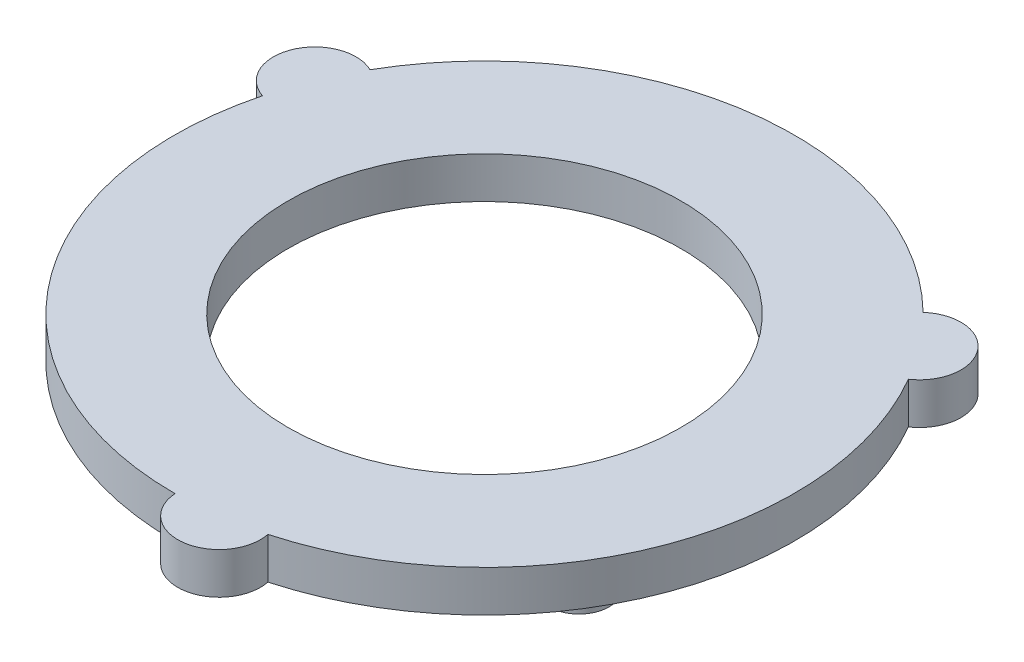
SolidWorks part; units mm, degrees
ref_plane "Спереди" through (0, 0, 0) normal (0, 0, 1) x (1, 0, 0)
ref_plane "Сверху" through (0, 0, 0) normal (0, 1, 0) x (1, 0, 0)
ref_plane "Справа" through (0, 0, 0) normal (1, 0, 0) x (0, 0, -1)
sketch "Sketch1" plane through (0, 0, 0) normal (0, 1, 0) x (1, 0, 0)
  circle A0 centre (0, 0) radius 19
  dimension "D1" = 38
extrude "Boss-Extrude1" add sketch "Sketch1" along normal blind 3.5
sketch "Sketch2" plane through (0, 0, 0) normal (0, 1, 0) x (1, 0, 0)
  circle A0 centre (0, 0) radius 30
  circle A1 centre (0, 0) radius 19
  circle A2 centre (0, 0) radius 25 construction
  circle A3 centre (0, 25) radius 2.8
  circle A4 centre (21.6506, -12.5) radius 2.8
  circle A5 centre (-21.6506, -12.5) radius 2.8
  point P16 (0, 0)
  dimension "D2" = 50
  dimension "D1" = 3
extrude "Boss-Extrude2" add sketch "Sketch2" along normal blind 4
sketch "Sketch3" plane through (0, 3.5, 0) normal (0, 1, 0) x (1, 0, 0)
  circle A0 centre (0, 0) radius 19
extrude "Cut-Extrude1" cut sketch "Sketch3" against normal blind 10
sketch "Sketch4" plane through (0, 0, 0) normal (0, -1, 0) x (1, 0, 0)
  circle A0 centre (-21.6506, 12.5) radius 2.9
  circle A1 centre (21.6506, 12.5) radius 2.9
  circle A2 centre (0, -25) radius 2.9
  point P9 (0, 0)
  dimension "D1" = 3
extrude "Boss-Extrude3" add sketch "Sketch4" along normal blind 2 and the other way up to surface (4 mm away) other way up to face at (21.6506, 4, 15.3)
sketch "Sketch5" plane through (0, 4, 0) normal (0, 1, 0) x (1, 0, 0)
  circle A0 centre (-27.7693, 11.3518) radius 4
  circle A1 centre (0, 0) radius 30 construction
  circle A2 centre (23.7156, 18.3731) radius 4
  circle A3 centre (4.0537, -29.7249) radius 4
  point P4 (-27.7693, 11.3518)
  point P10 (0, 0)
  dimension "D1" = 3
extrude "Boss-Extrude4" add sketch "Sketch5" against normal up to surface (4 mm away) up to face at (0, 0, -22.1)
